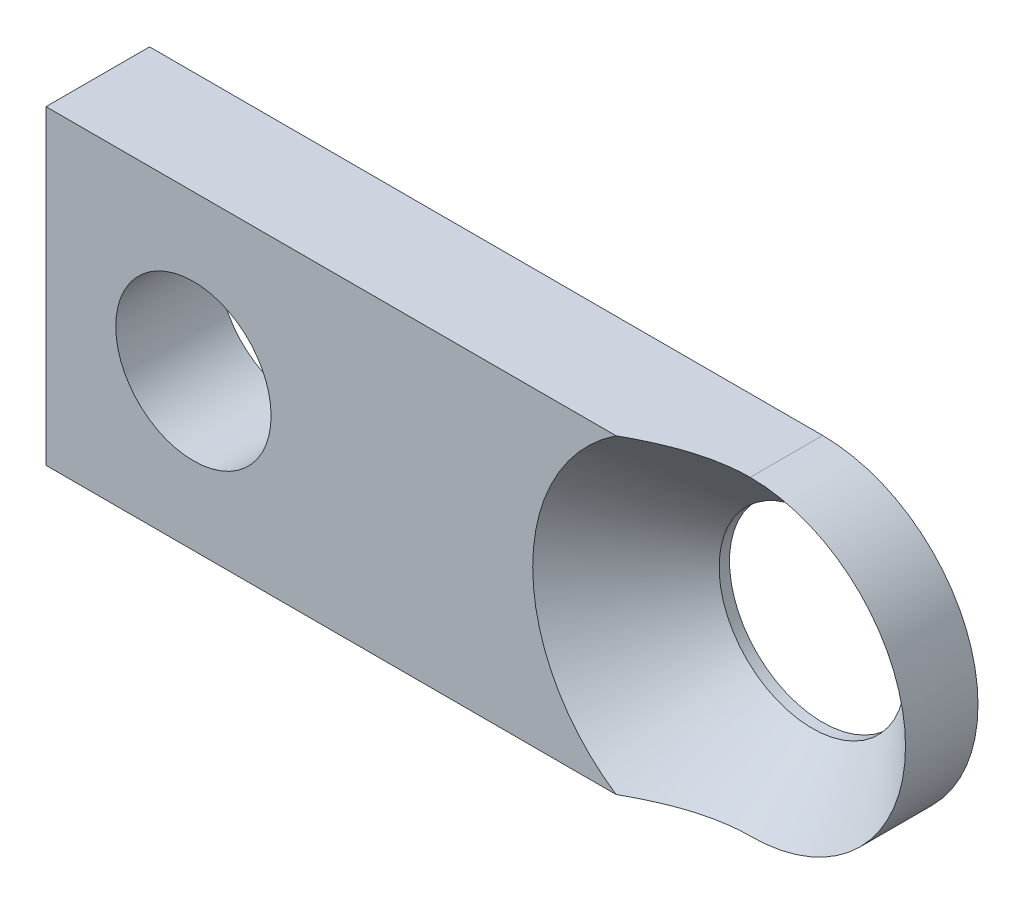
SolidWorks part; units mm, degrees
ref_plane "Front Plane" through (0, 0, 0) normal (0, 0, 1) x (1, 0, 0)
ref_plane "Top Plane" through (0, 0, 0) normal (0, 1, 0) x (1, 0, 0)
ref_plane "Right Plane" through (0, 0, 0) normal (1, 0, 0) x (0, 0, -1)
sketch "Sketch1" plane through (0, 0, 0) normal (0, 0, 1) x (1, 0, 0)
  line L1 (1.7765, 1.5) -> (0.2765, 1.5)
  line L3 (1.7765, -1.5) -> (0.2765, -1.5)
  line L4 (0.2765, 1.5) -> (0.2765, -1.5)
  line L5 (1.7765, 1.5) -> (0.2765, -1.5) construction
  line L6 (1.7765, -1.5) -> (0.2765, 1.5) construction
  arc A1 (1.7765, -1.5) -> (1.7765, 1.5) centre (1.7765, 0) ccw
  circle A2 centre (1.7765, 0) radius 1.5 construction
extrude "Boss-Extrude1" add sketch "Sketch1" along normal blind 1
sketch "Sketch3" plane through (0.2765, 0, 0) normal (-1, 0, 0) x (0, 0, 1)
  line L1 (0, -1.5) -> (1, -1.5)
  line L2 (0, -1.5) -> (0, 1.5)
  line L3 (0, 1.5) -> (1, 1.5)
  line L4 (1, -1.5) -> (1, 1.5)
extrude "Boss-Extrude2" add sketch "Sketch3" along normal blind 5
hole_wizard "Ø1.5mm Dowel Hole1" positions "Sketch6" profile "Sketch5" hole size "Ø1.5" standard "ISO" end condition up to next
sketch "Sketch6" plane through (0, 0, 0) normal (0, 0, -1) x (-1, 0, 0)
  line L0 (3.3, 0.35) -> (3.3, -1.05) construction
  point P0 (3.3, 0)
sketch "Sketch5" plane through (-3.3, 0, 0) normal (1, 0, 0) x (0, 1, 0)
  line L0 (0, 0) -> (0, 1)
  line L1 (0, 1) -> (0.75, 1)
  line L2 (0.75, 1) -> (0.75, 0)
  line L5 (0.75, 0) -> (0, 0)
  line L11 (0, -6.35) -> (0, 107.95) construction
  dimension "Thru Hole Dia." = 1.5
  dimension "Thru Hole Depth" = 1
hole_wizard "CSK SLOT for M1.6 Countersunk Flat Head Screw1" positions "Sketch7" profile "Sketch8" size "M1.6" standard "ISO" slot yes end condition up to next
sketch "Sketch7" plane through (0, 0, 1) normal (0, 0, 1) x (1, 0, 0)
  point P0 (1.7765, 0)
sketch "Sketch8" plane through (1.7765, 0, 1) normal (1, 0, 0) x (0, -1, 0)
  line L0 (0, 0) -> (0, 1)
  line L1 (0, 1) -> (0.9, 1)
  line L2 (0.9, 1) -> (0.9, 0.9)
  line L3 (0.9, 0.9) -> (1.8, 0)
  line L5 (1.8, 0) -> (0, 0)
  line L6 (-0.9, 0.9) -> (-1.8, 0) construction
  line L11 (0, -6.35) -> (0, 107.95) construction
  dimension "Thru Hole Dia." = 1.8
  dimension "Thru Hole Depth" = 1
  dimension "Near C'Sink Dia." = 3.6
  dimension "Near C'Sink Angle" = 90
